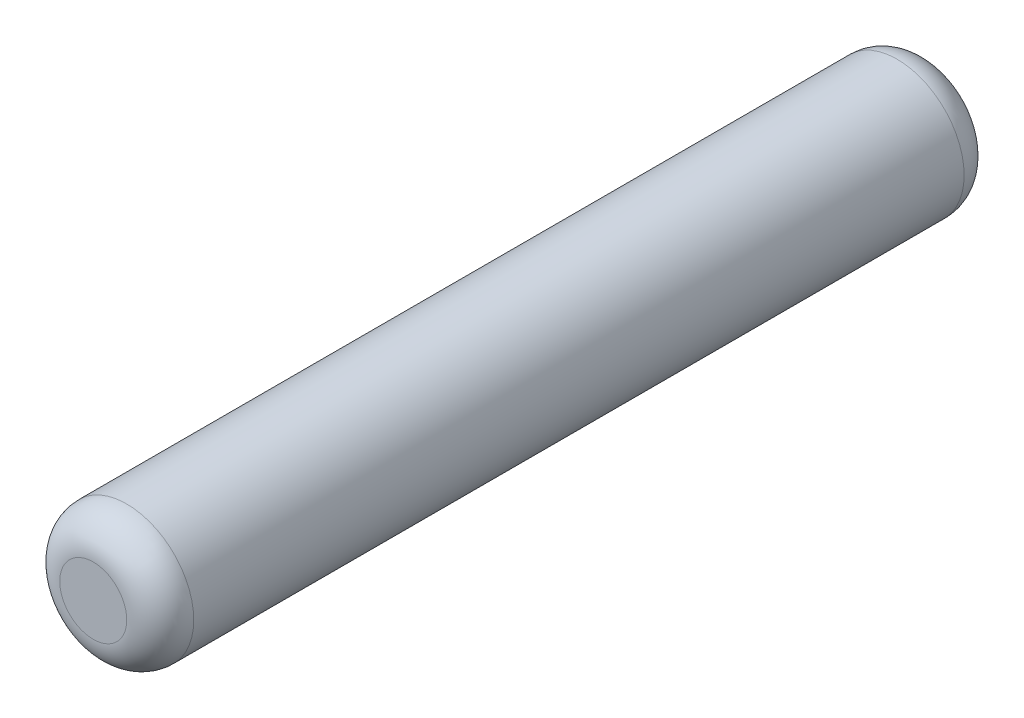
SolidWorks part; units mm, degrees
ref_plane "Front Plane" through (0, 0, 0) normal (0, 0, 1) x (1, 0, 0)
ref_plane "Top Plane" through (0, 0, 0) normal (0, 1, 0) x (1, 0, 0)
ref_plane "Right Plane" through (0, 0, 0) normal (1, 0, 0) x (0, 0, -1)
sketch "Sketch1" plane through (0, 0, 0) normal (0, 0, 1) x (1, 0, 0)
  circle A0 centre (0, 0) radius 20
  dimension "D1" = 40
extrude "Boss-Extrude1" add sketch "Sketch1" along normal blind 250
fillet "Fillet1" radius 10 2 edges at (20, 0, 0) (20, 0, 250)
